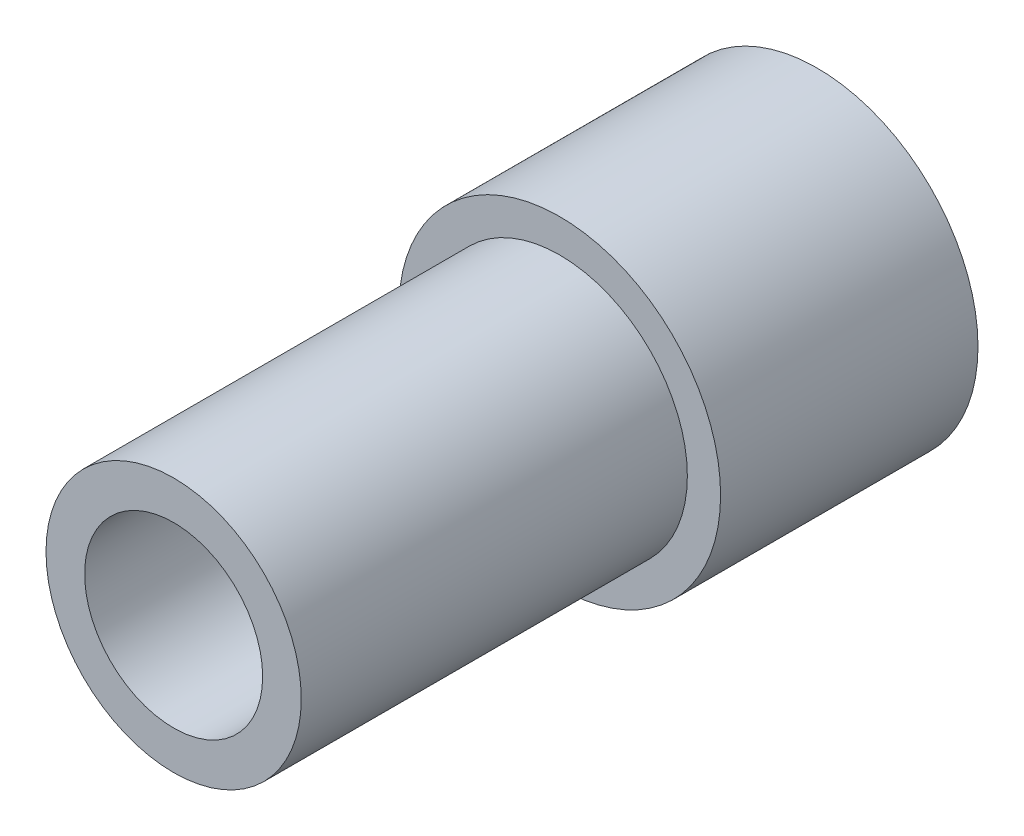
SolidWorks part; units mm, degrees
ref_plane "Front Plane" through (0, 0, 0) normal (0, 0, 1) x (1, 0, 0)
ref_plane "Top Plane" through (0, 0, 0) normal (0, 1, 0) x (1, 0, 0)
ref_plane "Right Plane" through (0, 0, 0) normal (1, 0, 0) x (0, 0, -1)
sketch "Sketch1" plane through (0, 0, 0) normal (0, 0, 1) x (1, 0, 0)
  circle A0 centre (0, 0) radius 7.5
  circle A1 centre (0, 0) radius 4.15
  dimension "D1" = 15
  dimension "D2" = 8.3
extrude "Boss-Extrude1" add sketch "Sketch1" along normal blind 30
sketch "Sketch2" plane through (0, 0, 30) normal (0, 0, 1) x (1, 0, 0)
  circle A0 centre (0, 0) radius 5.95
  circle A1 centre (0, 0) radius 7.5
  circle A2 centre (0, 0) radius 7.5 construction
  dimension "D1" = 11.9
extrude "Cut-Extrude1" cut sketch "Sketch2" against normal blind 18
